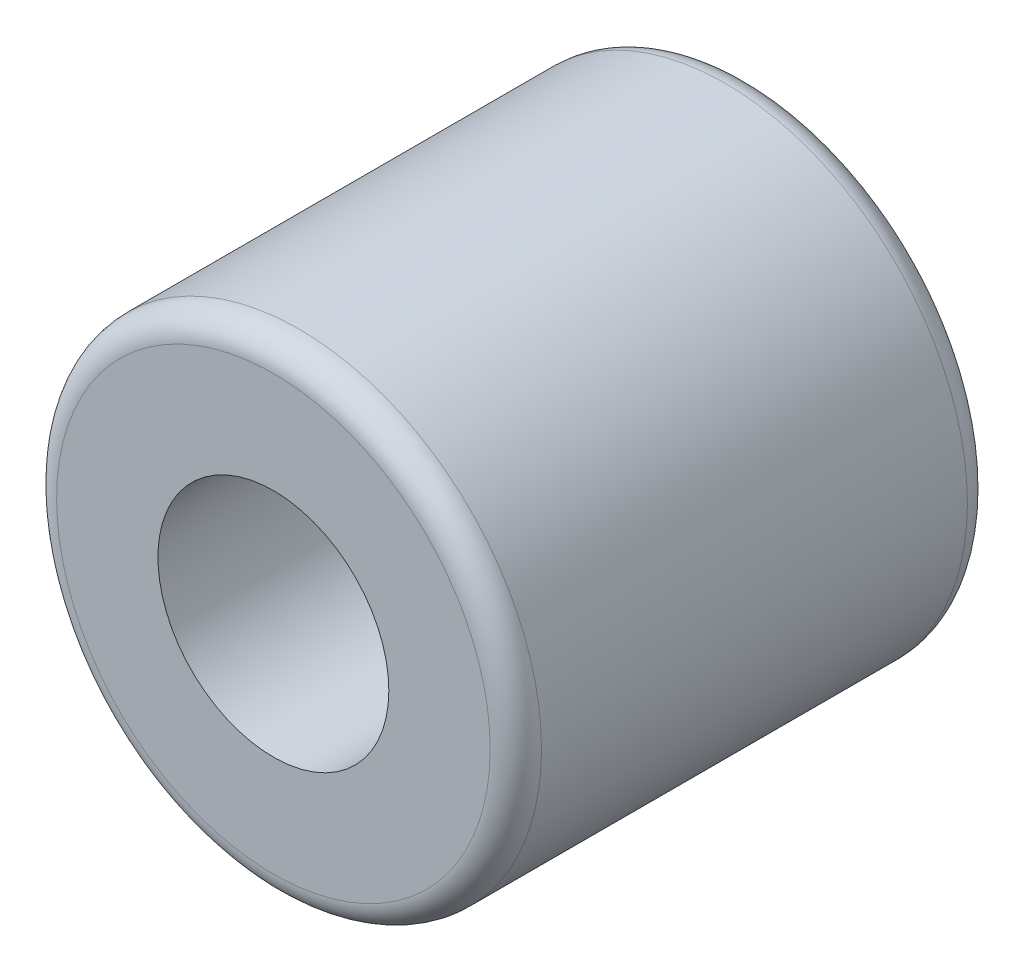
SolidWorks part; units mm, degrees
ref_plane "正面" through (0, 0, 0) normal (0, 0, 1) x (1, 0, 0)
ref_plane "平面" through (0, 0, 0) normal (0, 1, 0) x (1, 0, 0)
ref_plane "右側面" through (0, 0, 0) normal (1, 0, 0) x (0, 0, -1)
sketch "ｽｹｯﾁ1" plane through (0, 0, 0) normal (0, 0, 1) x (1, 0, 0)
  circle A0 centre (0, 0) radius 9.45
  circle A1 centre (0, 0) radius 4.5
  dimension "D1" = 18.9
  dimension "D2" = 9
extrude "ﾎﾞｽ - 押し出し1" add sketch "ｽｹｯﾁ1" along normal blind 18.6
fillet "ﾌｨﾚｯﾄ1" radius 1 2 edges at (9.45, 0, 0) (9.45, 0, 18.6)
